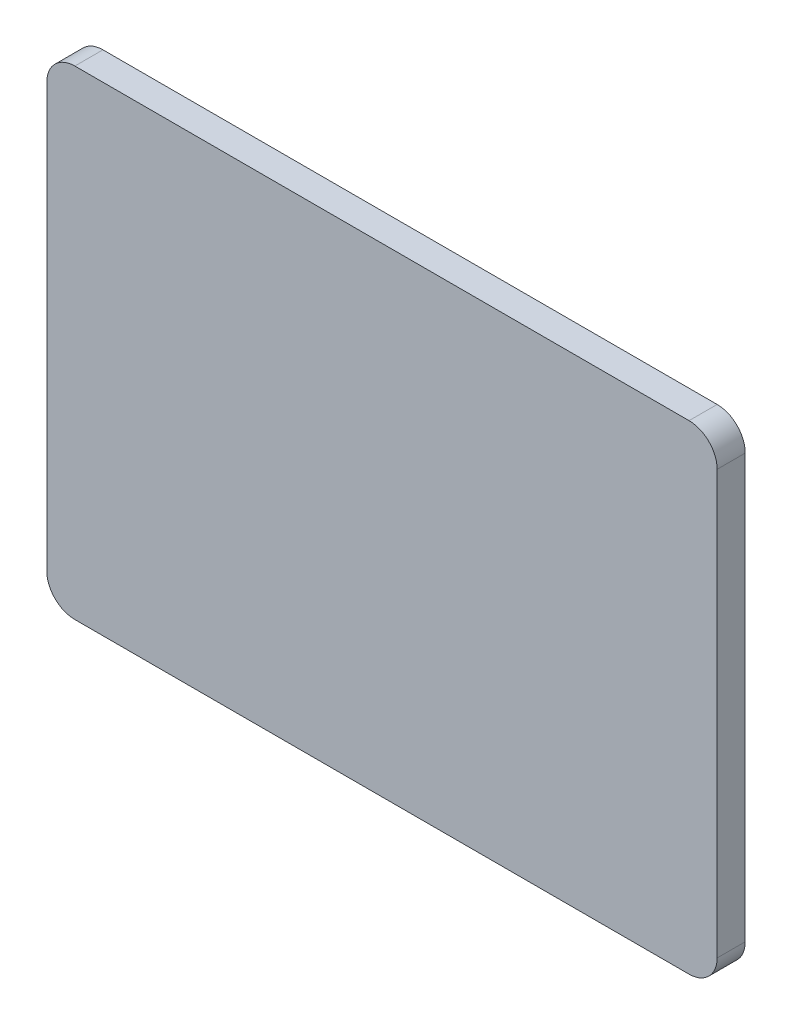
SolidWorks part; units mm, degrees
ref_plane "Plan de face" through (0, 0, 0) normal (0, 0, 1) x (1, 0, 0)
ref_plane "Plan de dessus" through (0, 0, 0) normal (0, 1, 0) x (1, 0, 0)
ref_plane "Plan de droite" through (0, 0, 0) normal (1, 0, 0) x (0, 0, -1)
sketch "Esquisse1" plane through (0, 0, 0) normal (0, 0, 1) x (1, 0, 0)
  line L1 (0, 0) -> (358, 0)
  line L2 (0, 0) -> (0, 256)
  line L3 (0, 256) -> (358, 256)
  line L4 (358, 0) -> (358, 256)
  dimension "D1" = 358
  dimension "D2" = 256
extrude "Boss.-Extru.1" add sketch "Esquisse1" along normal blind 15
fillet "Congé1" radius 15 4 edges at (0, 0, 7.5) (358, 0, 7.5) (358, 256, 7.5) (0, 256, 7.5)
